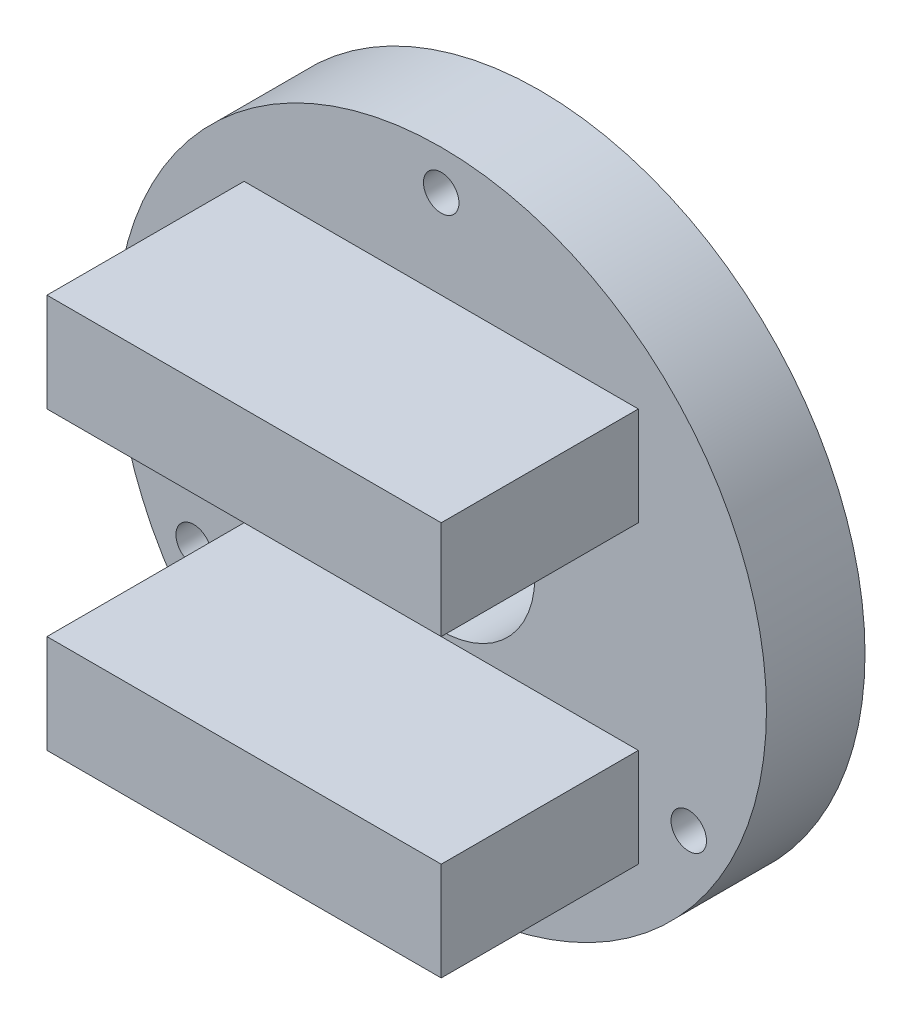
SolidWorks part; units mm, degrees
ref_plane "前视基准面" through (0, 0, 0) normal (0, 0, 1) x (1, 0, 0)
ref_plane "上视基准面" through (0, 0, 0) normal (0, 1, 0) x (1, 0, 0)
ref_plane "右视基准面" through (0, 0, 0) normal (1, 0, 0) x (0, 0, -1)
other "Configuration Table"
sketch "草图1" plane through (0, 0, 0) normal (0, 0, 1) x (1, 0, 0)
  circle A0 centre (0, 0) radius 33
  circle A1 centre (0, 0) radius 29 construction
  circle A2 centre (0, 29) radius 1.8
  circle A3 centre (25.1147, -14.5) radius 1.8
  circle A4 centre (-25.1147, -14.5) radius 1.8
  circle A5 centre (0, 0) radius 9.5
  dimension "D1" = 66
  dimension "D2" = 58
  dimension "D3" = 3.6
  dimension "D5" = 19
  dimension "D4" = 3
extrude "凸台-拉伸1" add sketch "草图1" along normal blind 10
sketch "草图2" plane through (0, 0, 10) normal (0, 0, 1) x (1, 0, 0)
  line L1 (-20, 20) -> (20, 20)
  line L2 (-20, 20) -> (-20, 10)
  line L3 (-20, 10) -> (20, 10)
  line L4 (20, 20) -> (20, 10)
  line L5 (-20, -10) -> (20, -10)
  line L6 (-20, -10) -> (-20, -20)
  line L7 (-20, -20) -> (20, -20)
  line L8 (20, -10) -> (20, -20)
  dimension "D1" = 20
  dimension "D2" = 10
  dimension "D3" = 10
  dimension "D4" = 10
  dimension "D5" = 40
  dimension "D6" = 20
extrude "凸台-拉伸2" add sketch "草图2" along normal blind 20
